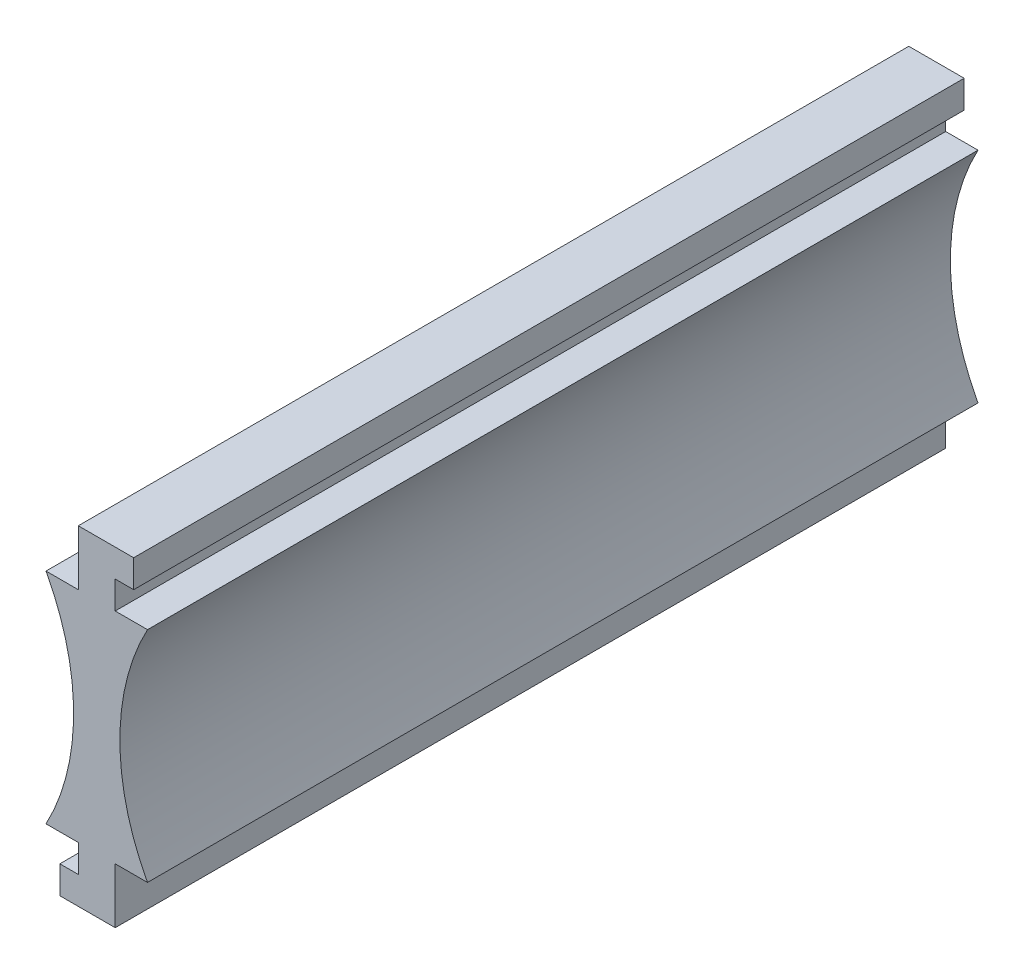
SolidWorks part; units mm, degrees
ref_plane "Спереди" through (0, 0, 0) normal (0, 0, 1) x (1, 0, 0)
ref_plane "Сверху" through (0, 0, 0) normal (0, 1, 0) x (1, 0, 0)
ref_plane "Справа" through (0, 0, 0) normal (1, 0, 0) x (0, 0, -1)
sketch "Эскиз1" plane through (0, 0, 0) normal (0, 0, 1) x (1, 0, 0)
  line L0 (-35.8073, 0) -> (44.0448, 0) construction
  line L28 (0, 75.256) -> (0, -88.7877) construction
  line L29 (-11, -23.725) -> (-4, -23.725)
  line L30 (4, -23.725) -> (11, -23.725)
  line L31 (4, -23.725) -> (4, -35.725)
  line L32 (4, -35.725) -> (-8, -35.725)
  line L33 (-8, -35.725) -> (-8, -29.725)
  line L34 (-8, -29.725) -> (-4, -29.725)
  line L35 (-4, -29.725) -> (-4, -23.725)
  line L36 (-11, 23.725) -> (-4, 23.725)
  line L37 (4, 23.725) -> (11, 23.725)
  line L38 (4, 23.725) -> (4, 29.725)
  line L39 (4, 29.725) -> (8, 29.725)
  line L40 (8, 29.725) -> (8, 35.725)
  line L41 (8, 35.725) -> (-4, 35.725)
  line L42 (-4, 35.725) -> (-4, 23.725)
  arc A4 (11, -23.725) -> (11, 23.725) centre (55.0128, 0) cw
  arc A5 (-11, -23.725) -> (-11, 23.725) centre (-55.0128, 0) ccw
  point P23 (0, 0)
  dimension "D1" = 12
  dimension "D7" = 47.45
  dimension "D9" = 6
  dimension "D6" = 50
  dimension "D2" = 4
  dimension "D3" = 6
  dimension "D4" = 12
  dimension "D5" = 22
  dimension "D8" = 12
  dimension "D10" = 4
  dimension "D11" = 12
  dimension "D12" = 22
  dimension "D13" = 8
extrude "Бобышка-Вытянуть1" add sketch "Эскиз1" against normal blind 180
